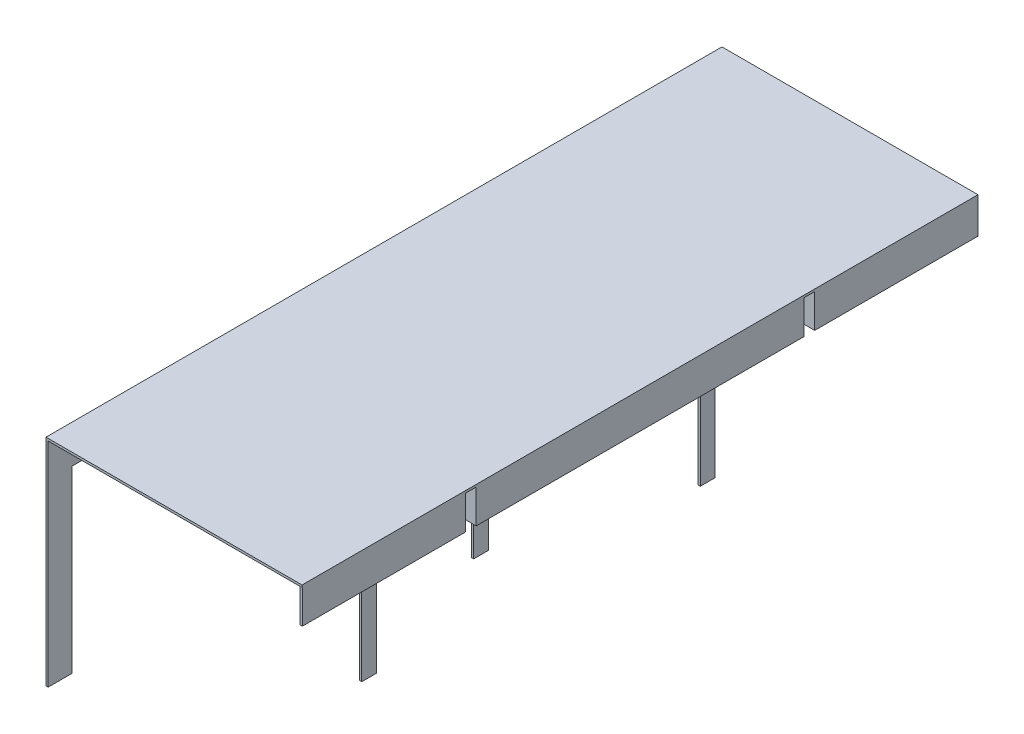
SolidWorks part; units mm, degrees
material "Pine"
ref_plane "Front Plane" through (0, 0, 0) normal (0, 0, 1) x (1, 0, 0)
ref_plane "Top Plane" through (0, 0, 0) normal (0, 1, 0) x (1, 0, 0)
ref_plane "Right Plane" through (0, 0, 0) normal (1, 0, 0) x (0, 0, -1)
sketch "Sketch1" plane through (0, 0, 0) normal (0, 1, 0) x (1, 0, 0)
  line L0 (0, 0) -> (0, 1386.84)
  line L1 (0, 1386.84) -> (-863.6, 1386.84)
  line L2 (-863.6, 1386.84) -> (-863.6, 1475.74)
  line L3 (-863.6, 1475.74) -> (0, 1475.74)
  line L4 (0, 1475.74) -> (0, 4262.12)
  line L5 (0, 4262.12) -> (-863.6, 4262.12)
  line L6 (-863.6, 4262.12) -> (-863.6, 4351.02)
  line L7 (-863.6, 4351.02) -> (0, 4351.02)
  line L8 (0, 4351.02) -> (0, 5737.86)
  line L11 (-19.05, 5718.81) -> (-19.05, 4370.07)
  line L12 (-19.05, 4370.07) -> (-882.65, 4370.07)
  line L13 (-882.65, 4370.07) -> (-882.65, 4243.07)
  line L14 (-882.65, 4243.07) -> (-19.05, 4243.07)
  line L15 (-19.05, 4243.07) -> (-19.05, 1494.79)
  line L16 (-19.05, 1494.79) -> (-882.65, 1494.79)
  line L17 (-882.65, 1494.79) -> (-882.65, 1367.79)
  line L18 (-882.65, 1367.79) -> (-19.05, 1367.79)
  line L19 (-19.05, 1367.79) -> (-19.05, 0)
  line L20 (-19.05, 0) -> (0, 0)
  line L21 (-863.6, 1431.29) -> (-882.65, 1431.29) construction
  line L22 (-431.8, 1386.84) -> (-431.8, 1367.79) construction
  line L23 (-19.05, 683.895) -> (0, 683.895) construction
  line L24 (-431.8, 1475.74) -> (-431.8, 1494.79) construction
  line L25 (-19.05, 2868.93) -> (0, 2868.93) construction
  line L26 (-431.8, 4262.12) -> (-431.8, 4243.07) construction
  line L27 (-863.6, 4306.57) -> (-882.65, 4306.57) construction
  line L28 (-450.85, 4370.07) -> (-450.85, 4351.02) construction
  line L29 (-19.05, 5044.44) -> (0, 5044.44) construction
  line L30 (0, 5737.86) -> (-889, 5737.86)
  line L31 (-889, 5737.86) -> (-889, 5718.81)
  line L32 (-889, 5718.81) -> (-19.05, 5718.81)
  dimension "D1" = 1386.84
  dimension "D2" = 2786.38
  dimension "D3" = 1386.84
  dimension "D4" = 88.9
  dimension "D5" = 88.9
  dimension "D6" = 863.6
  dimension "D7" = 863.6
  dimension "D8" = 19.05
  dimension "D9" = 889
extrude "Boss-Extrude1" add sketch "Sketch1" along normal blind 304.8
sketch "Sketch2" plane through (0, 304.8, 0) normal (0, 1, 0) x (1, 0, 0)
  line L1 (0, 5737.86) -> (-2174.24, 5737.86)
  line L2 (0, 5737.86) -> (0, -2.54)
  line L3 (0, -2.54) -> (-2174.24, -2.54)
  line L4 (-2174.24, 5737.86) -> (-2174.24, -2.54)
  dimension "D1" = 2174.24
  dimension "D2" = 5740.4
extrude "Boss-Extrude2" add sketch "Sketch2" against normal blind 19.05
sketch "Sketch3" plane through (0, 285.75, 0) normal (0, -1, 0) x (1, 0, 0)
  line L0 (-2174.24, 2.54) -> (-2174.24, -2766.06)
  line L2 (-2174.24, -2766.06) -> (-1310.64, -2766.06)
  line L3 (-1310.64, -2766.06) -> (-1310.64, -2854.96)
  line L4 (-1310.64, -2854.96) -> (-2174.24, -2854.96)
  line L5 (-2174.24, -2854.96) -> (-2174.24, -5737.86)
  line L6 (-2174.24, -5737.86) -> (-2155.19, -5737.86)
  line L7 (-889, -5737.86) -> (-2174.24, -5737.86) construction
  line L8 (-2155.19, -5737.86) -> (-2155.19, -2874.01)
  line L9 (-2155.19, -2874.01) -> (-1291.59, -2874.01)
  line L10 (-1291.59, -2874.01) -> (-1291.59, -2747.01)
  line L11 (-1291.59, -2747.01) -> (-2155.19, -2747.01)
  line L12 (-2155.19, -2747.01) -> (-2155.19, 2.54)
  line L13 (-2174.24, 2.54) -> (0, 2.54) construction
  line L14 (-2155.19, 2.54) -> (-2174.24, 2.54)
  dimension "D1" = 19.05
  dimension "D2" = 19.05
  dimension "D3" = 19.05
  dimension "D4" = 19.05
  dimension "D5" = 19.05
  dimension "D6" = 88.9
  dimension "D7" = 863.6
  dimension "D8" = 2768.6
extrude "Boss-Extrude3" add sketch "Sketch3" along normal blind 285.75
sketch "Sketch4" plane through (0, 0, 0) normal (0, -1, 0) x (1, 0, 0)
  line L0 (-882.65, -1494.79) -> (-19.05, -1494.79) construction
  line L1 (-882.65, -1367.79) -> (-863.6, -1367.79)
  line L2 (-882.65, -1367.79) -> (-882.65, -1494.79)
  line L3 (-882.65, -1494.79) -> (-863.6, -1494.79)
  line L4 (-863.6, -1367.79) -> (-863.6, -1494.79)
  line L5 (-2155.19, -2874.01) -> (-1291.59, -2874.01) construction
  line L6 (-1291.59, -2747.01) -> (-1310.64, -2747.01)
  line L7 (-1291.59, -2747.01) -> (-1291.59, -2874.01)
  line L8 (-1291.59, -2874.01) -> (-1310.64, -2874.01)
  line L9 (-1310.64, -2747.01) -> (-1310.64, -2874.01)
  line L10 (-19.05, -4370.07) -> (-882.65, -4370.07) construction
  line L11 (-882.65, -4243.07) -> (-863.6, -4243.07)
  line L12 (-882.65, -4243.07) -> (-882.65, -4370.07)
  line L13 (-882.65, -4370.07) -> (-863.6, -4370.07)
  line L14 (-863.6, -4243.07) -> (-863.6, -4370.07)
  dimension "D1" = 19.05
  dimension "D2" = 19.05
  dimension "D3" = 19.05
extrude "Boss-Extrude4" add sketch "Sketch4" along normal blind 1524
sketch "Sketch5" plane through (-2155.19, 0, 0) normal (1, 0, 0) x (0, 0, -1)
  line L1 (5737.86, 304.8) -> (5718.81, 304.8)
  line L2 (5737.86, 304.8) -> (5737.86, -1981.2)
  line L3 (5737.86, -1981.2) -> (5718.81, -1981.2)
  line L4 (5718.81, 304.8) -> (5718.81, -1981.2)
  dimension "D1" = 19.05
  dimension "D2" = 2286
extrude "Boss-Extrude5" add sketch "Sketch5" along normal blind 152.4
sketch "Sketch6" plane through (0, 0, -5737.86) normal (0, 0, -1) x (-1, 0, 0)
  line L1 (2155.19, 0) -> (2174.24, 0)
  line L2 (2155.19, 0) -> (2155.19, -1524)
  line L3 (2155.19, -1524) -> (2174.24, -1524)
  line L4 (2174.24, 0) -> (2174.24, -1524)
  dimension "D1" = 1524
extrude "Boss-Extrude6" add sketch "Sketch6" against normal up to surface (5740.4 mm away) up to face at (-1443.1433, 196.85, 2.54)
sketch "Sketch7" plane through (-2155.19, 0, 0) normal (1, 0, 0) x (0, 0, -1)
  line L0 (5718.81, 285.75) -> (5718.81, -1524) construction
  line L1 (200.66, 0) -> (5312.41, 0)
  line L2 (200.66, 0) -> (200.66, -1524)
  line L3 (200.66, -1524) -> (5312.41, -1524)
  line L4 (5312.41, 0) -> (5312.41, -1524)
  line L5 (-2.54, -1524) -> (-2.54, 285.75) construction
  dimension "D1" = 406.4
  dimension "D2" = 203.2
extrude "Cut-Extrude1" cut sketch "Sketch7" against normal through all
